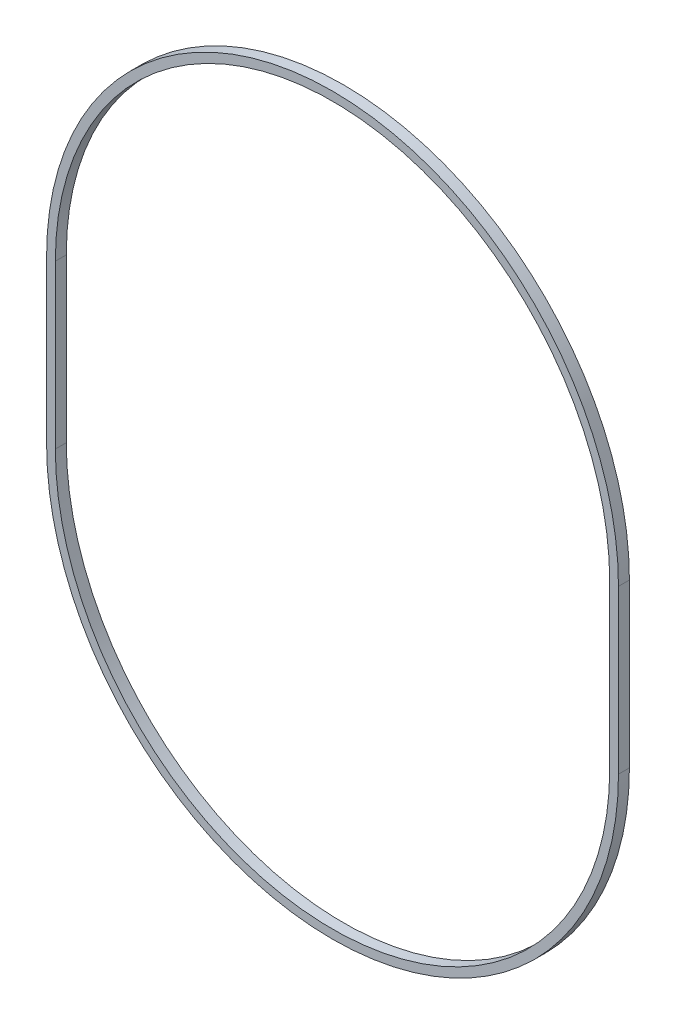
SolidWorks part; units mm, degrees
ref_plane "Front Plane" through (0, 0, 0) normal (0, 0, 1) x (1, 0, 0)
ref_plane "Top Plane" through (0, 0, 0) normal (0, 1, 0) x (1, 0, 0)
ref_plane "Right Plane" through (0, 0, 0) normal (1, 0, 0) x (0, 0, -1)
sketch "Sketch1" plane through (0, 0, 0) normal (0, 0, 1) x (1, 0, 0)
  line B0 (-127.19, 27.875) -> (-127.19, -27.875)
  line B1 (-98, 27.875) -> (-98, -27.875)
  line B2 (98, -27.875) -> (98, 27.875)
  line B3 (-127.19, 27.875) -> (-127.19, -27.875)
  line B4 (127.19, -27.875) -> (127.19, 27.875)
  line B5 (124.19, -27.875) -> (124.19, 27.875)
  line B6 (-124.19, 27.875) -> (-124.19, -27.875)
  line B7 (95, -27.875) -> (95, 27.875)
  line B8 (-95, 27.875) -> (-95, -27.875)
  arc B9 (-98, -27.875) -> (98, -27.875) centre (0, -27.875) ccw
  arc B10 (98, 27.875) -> (-98, 27.875) centre (0, 27.875) ccw
  arc B11 (127.19, 27.875) -> (-127.19, 27.875) centre (0, 27.875) ccw
  arc B12 (-127.19, -27.875) -> (127.19, -27.875) centre (0, -27.875) ccw
  arc B13 (124.19, 27.875) -> (-124.19, 27.875) centre (0, 27.875) ccw
  arc B14 (-124.19, -27.875) -> (124.19, -27.875) centre (0, -27.875) ccw
  arc B15 (127.19, 27.875) -> (-127.19, 27.875) centre (0, 27.875) ccw
  arc B16 (124.19, 27.875) -> (-124.19, 27.875) centre (0, 27.875) ccw
  arc B17 (95, 27.875) -> (-95, 27.875) centre (0, 27.875) ccw
  arc B18 (95, 27.875) -> (-95, 27.875) centre (0, 27.875) ccw
  arc B19 (-95, -27.875) -> (95, -27.875) centre (0, -27.875) ccw
sketch_block_instance "Gasket Rims-1"
sketch_block "Gasket Rims"
extrude "Boss-Extrude1" add sketch "Sketch1" along normal mid plane 3.75 contours B2 B10 B1 B9 B19 B8 B17 B7 | B13
